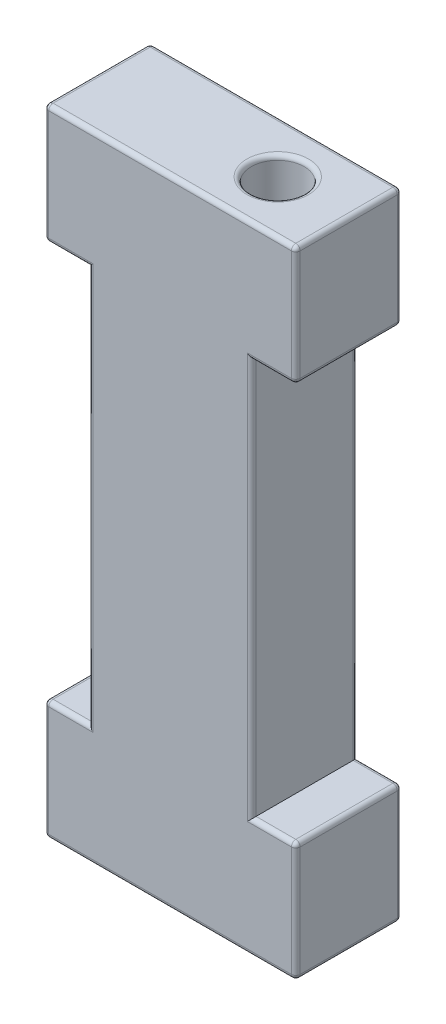
SolidWorks part; units mm, degrees
material "Balsa"
ref_plane "Plano frontal" through (0, 0, 0) normal (0, 0, 1) x (1, 0, 0)
ref_plane "Plano superior" through (0, 0, 0) normal (0, 1, 0) x (1, 0, 0)
ref_plane "Plano direito" through (0, 0, 0) normal (1, 0, 0) x (0, 0, -1)
sketch "Esboço1" plane through (0, 0, 0) normal (0, 1, 0) x (1, 0, 0)
  line L1 (-14.25, -6) -> (14.25, -6)
  line L2 (-14.25, -6) -> (-14.25, 6)
  line L3 (-14.25, 6) -> (14.25, 6)
  line L4 (14.25, -6) -> (14.25, 6)
  line L5 (-14.25, -6) -> (14.25, 6) construction
  line L6 (-14.25, 6) -> (14.25, -6) construction
  circle A0 centre (6.2057, 0) radius 3
  point P0 (0, 0)
  dimension "D3" = 6
  dimension "D1" = 28.5
  dimension "D2" = 12
  dimension "D4" = 20.4557
extrude "Ressalto-extrusão1" add sketch "Esboço1" along normal mid plane 72
sketch "Esboço2" plane through (0, 0, 0) normal (0, 0, 1) x (1, 0, 0)
  line L0 (-14.25, 36) -> (-14.25, -36) construction
  line L1 (-19.25, 22.5) -> (-9.25, 22.5)
  line L2 (-19.25, 22.5) -> (-19.25, -22.5)
  line L3 (-19.25, -22.5) -> (-9.25, -22.5)
  line L4 (-9.25, 22.5) -> (-9.25, -22.5)
  line L5 (-19.25, 22.5) -> (-9.25, -22.5) construction
  line L6 (-19.25, -22.5) -> (-9.25, 22.5) construction
  line L7 (0, 44.3868) -> (0, -49.4435) construction
  line L8 (19.25, -22.5) -> (9.25, 22.5) construction
  line L9 (19.25, 22.5) -> (9.25, -22.5) construction
  line L10 (9.25, 22.5) -> (9.25, -22.5)
  line L11 (19.25, -22.5) -> (9.25, -22.5)
  line L12 (19.25, 22.5) -> (19.25, -22.5)
  line L13 (19.25, 22.5) -> (9.25, 22.5)
  point P0 (-14.25, 0)
  point P14 (14.25, 0)
  dimension "D1" = 45
  dimension "D2" = 10
extrude "Corte-extrusão1" cut sketch "Esboço2" against normal mid plane 20
fillet "Filete1" radius 0.5 34 edges at (14.25, -29.25, -6) (14.25, 29.25, -6) (-14.25, -29.25, -6) (-14.25, 29.25, -6) (-14.25, 29.25, 6) (-14.25, -29.25, 6) (14.25, -29.25, 6) (14.25, 29.25, 6) (0, 36, 6) (-14.25, 36, 0) (0, 36, -6) (14.25, 36, 0) (0, -36, -6) (-14.25, -36, 0) (0, -36, 6) (14.25, -36, 0) (6.2057, -36, 3) (6.2057, 36, 3) (-11.75, 22.5, -6) (-9.25, 0, -6) (-11.75, -22.5, -6) (-14.25, 22.5, 0) (-11.75, 22.5, 6) (-11.75, -22.5, 6) (-9.25, 0, 6) (-14.25, -22.5, 0) (14.25, 22.5, 0) (11.75, 22.5, -6) (11.75, -22.5, -6) (9.25, 0, -6) (11.75, 22.5, 6) (9.25, 0, 6) (11.75, -22.5, 6) (14.25, -22.5, 0)
